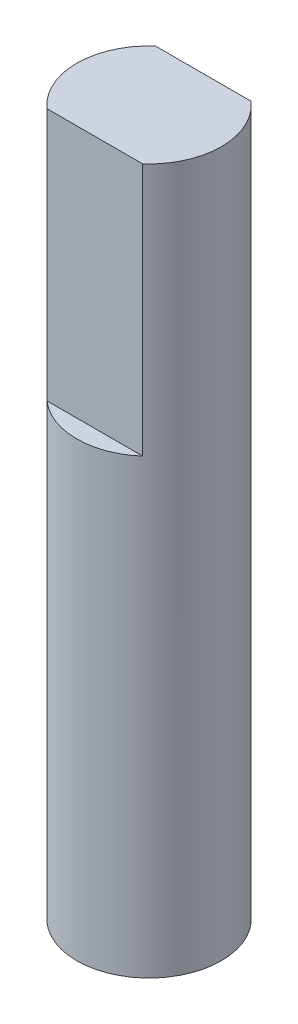
SolidWorks part; units mm, degrees
ref_plane "Alzado" through (0, 0, 0) normal (0, 0, 1) x (1, 0, 0)
ref_plane "Planta" through (0, 0, 0) normal (0, 1, 0) x (1, 0, 0)
ref_plane "Vista lateral" through (0, 0, 0) normal (1, 0, 0) x (0, 0, -1)
sketch "Croquis1" plane through (0, 0, 0) normal (0, 1, 0) x (1, 0, 0)
  circle A2 centre (0, 0) radius 4
  dimension "D1" = 8
extrude "Saliente-Extruir1" add sketch "Croquis1" along normal blind 25
sketch "Croquis2" plane through (0, 25, 0) normal (0, 1, 0) x (1, 0, 0)
  line L1 (-2.6458, -3) -> (2.6458, -3)
  line L3 (-2.6458, 3) -> (2.6458, 3)
  line L5 (-3.4581, -2.0104) -> (3.4581, 2.0104) construction
  line L6 (-3.4581, 2.0104) -> (3.4581, -2.0104) construction
  arc A0 (2.6458, -3) -> (2.6458, 3) centre (0, 0) ccw
  arc A1 (-2.6458, 3) -> (-2.6458, -3) centre (0, 0) ccw
extrude "Saliente-Extruir2" add sketch "Croquis2" along normal blind 14
